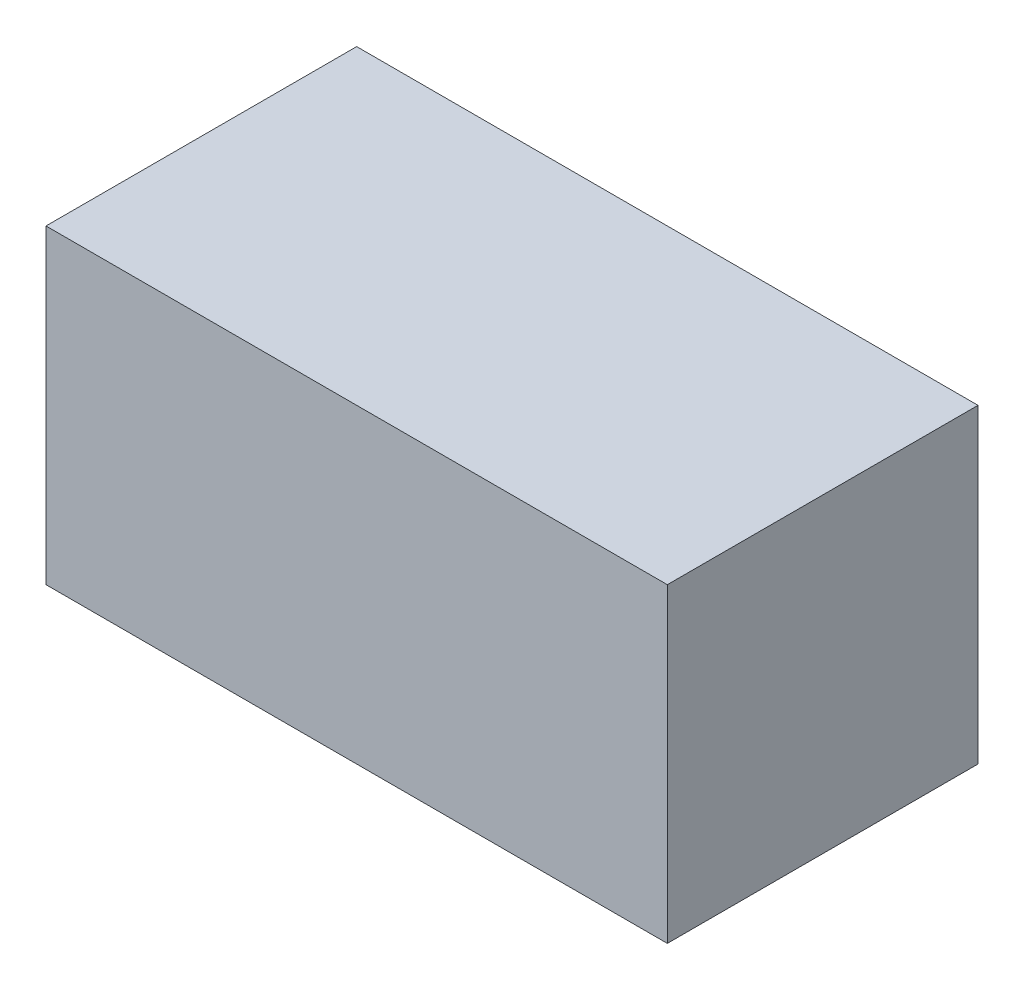
SolidWorks part; units mm, degrees
ref_plane "Front Plane" through (0, 0, 0) normal (0, 0, 1) x (1, 0, 0)
ref_plane "Top Plane" through (0, 0, 0) normal (0, 1, 0) x (1, 0, 0)
ref_plane "Right Plane" through (0, 0, 0) normal (1, 0, 0) x (0, 0, -1)
sketch "Sketch1" plane through (0, 0, 0) normal (0, 1, 0) x (1, 0, 0)
  line L1 (0, 0) -> (100, 0)
  line L2 (0, 0) -> (0, 50)
  line L3 (0, 50) -> (100, 50)
  line L4 (100, 0) -> (100, 50)
  dimension "D1" = 100
  dimension "D2" = 50
extrude "Boss-Extrude1" add sketch "Sketch1" along normal blind 50
